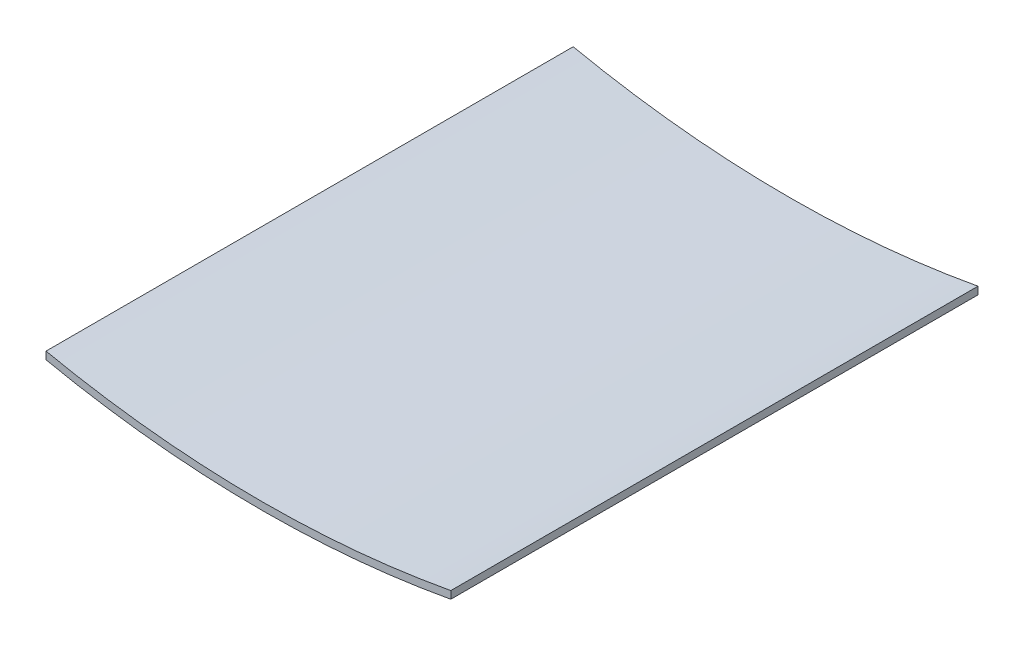
SolidWorks part; units mm, degrees
material "Acrylic (Medium-high impact)"
ref_plane "Front Plane" through (0, 0, 0) normal (0, 0, 1) x (1, 0, 0)
ref_plane "Top Plane" through (0, 0, 0) normal (0, 1, 0) x (1, 0, 0)
ref_plane "Right Plane" through (0, 0, 0) normal (1, 0, 0) x (0, 0, -1)
sketch "Sketch1" plane through (0, 0, 0) normal (0, 0, 1) x (1, 0, 0)
  line L2 (204.7875, -2.5114) -> (204.7875, -7.5914)
  line L3 (0, 0) -> (0, -5.08)
  arc A0 (204.7875, -2.5114) -> (0, 0) centre (108.7438, 516.5462) cw
  arc A1 (204.7875, -7.5914) -> (0, -5.08) centre (108.7438, 511.4662) cw
  dimension "D1" = 2
extrude "Boss-Extrude1" add sketch "Sketch1" along normal blind 266.7
sketch "Sketch2" plane through (0, 0, 0) normal (0, 0, -1) x (-1, 0, 0)
  line L0 (-204.7875, -2.5114) -> (-204.7875, -7.5914)
  line L1 (0, -5.08) -> (0, 0)
  arc A0 (-204.7875, -2.5114) -> (0, 0) centre (-108.7438, 516.5462) ccw
  arc A1 (-204.7875, -7.5914) -> (0, -5.08) centre (-108.7438, 511.4662) ccw
  arc A2 (-204.7875, -3.7814) -> (0, -1.27) centre (-108.7438, 515.2762) ccw
  arc M1 (0, 0) -> (-204.7875, -2.5114) centre (-108.7438, 516.5462) cw
  line M2 (-204.7875, -2.5114) -> (-204.7875, -7.5914)
  dimension "D1" = 2
extrude "Cut-Extrude1" cut sketch "Sketch2" against normal blind 304.8 contours A2 L1 M2 M1
